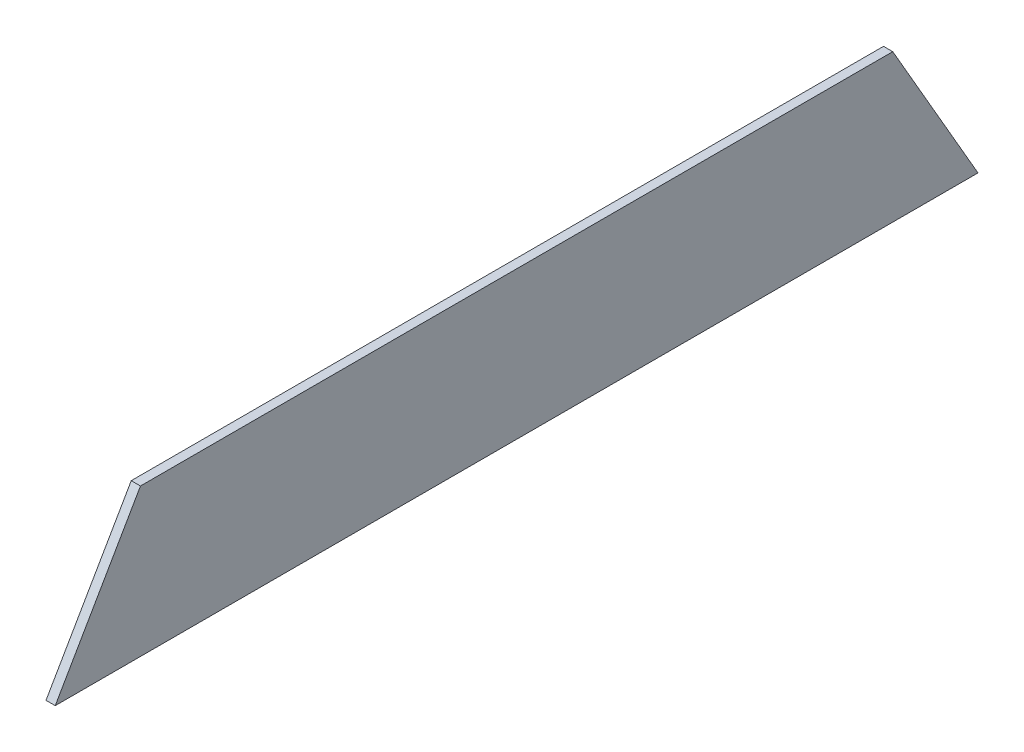
SolidWorks part; units mm, degrees
material "PE High Density Film"
ref_plane "Front Plane" through (0, 0, 0) normal (0, 0, 1) x (1, 0, 0)
ref_plane "Top Plane" through (0, 0, 0) normal (0, 1, 0) x (1, 0, 0)
ref_plane "Right Plane" through (0, 0, 0) normal (1, 0, 0) x (0, 0, -1)
sketch "Sketch1" plane through (0, 0, 0) normal (1, 0, 0) x (0, 0, -1)
  line L0 (-158.75, 0) -> (-144.0853, 25.4)
  line L1 (0, 0) -> (-158.75, 0)
  line L3 (-14.6647, 25.4) -> (-144.0853, 25.4)
  line L5 (0, 0) -> (-14.6647, 25.4)
  dimension "D1" = 25.4
  dimension "D2" = 158.75
  dimension "D3" = 60
  dimension "D4" = 60
extrude "Boss-Extrude1" add sketch "Sketch1" along normal blind 1.5875
